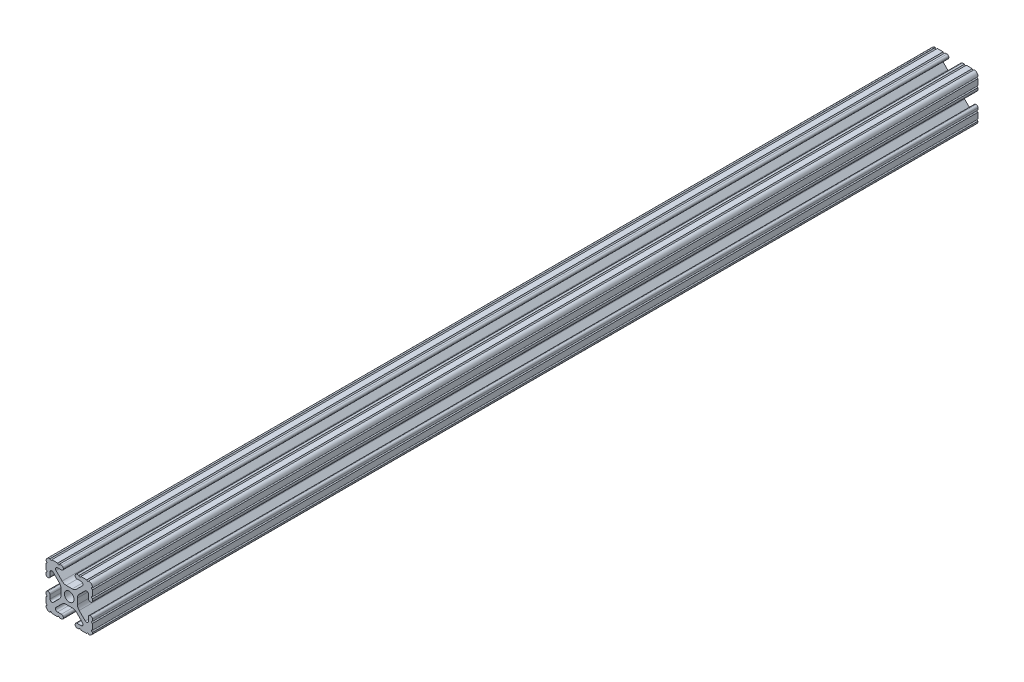
SolidWorks part; units mm, degrees
ref_plane "Front Plane" through (0, 0, 0) normal (0, 0, 1) x (1, 0, 0)
ref_plane "Top Plane" through (0, 0, 0) normal (0, 1, 0) x (1, 0, 0)
ref_plane "Right Plane" through (0, 0, 0) normal (1, 0, 0) x (0, 0, -1)
sketch "Sketch1" plane through (0, 0, 0) normal (0, 0, 1) x (1, 0, 0)
  line L88 (-7.1797, -8.6452) -> (-3.9523, -5.4237)
  line L89 (-1.7093, -4.4958) -> (1.7093, -4.4958)
  line L90 (3.9523, -5.4237) -> (7.1797, -8.6452)
  line L91 (6.4164, -10.4902) -> (4.2875, -10.4902)
  line L92 (3.2385, -11.5392) -> (3.2385, -11.651)
  line L93 (4.2875, -12.7) -> (5.3171, -12.7)
  line L94 (6.3331, -12.7) -> (9.5504, -12.7)
  line L95 (12.7, -9.5504) -> (12.7, -6.3331)
  line L96 (12.7, -5.3171) -> (12.7, -4.2875)
  line L97 (11.651, -3.2385) -> (11.5392, -3.2385)
  line L98 (10.4902, -4.2875) -> (10.4902, -6.4021)
  line L99 (8.7371, -7.1294) -> (5.441, -3.8408)
  line L100 (4.5085, -1.5932) -> (4.5085, 1.5932)
  line L101 (5.441, 3.8408) -> (8.7371, 7.1294)
  line L102 (10.4902, 6.4021) -> (10.4902, 4.2875)
  line L103 (11.5392, 3.2385) -> (11.651, 3.2385)
  line L104 (12.7, 4.2875) -> (12.7, 5.3171)
  line L105 (12.7, 6.3331) -> (12.7, 9.5504)
  line L106 (9.5504, 12.7) -> (6.3331, 12.7)
  line L107 (5.3171, 12.7) -> (4.2875, 12.7)
  line L108 (3.2385, 11.651) -> (3.2385, 11.5392)
  line L109 (4.2875, 10.4902) -> (6.4768, 10.4902)
  line L110 (7.207, 8.7244) -> (3.8983, 5.4232)
  line L111 (1.6558, 4.4958) -> (-1.6558, 4.4958)
  line L112 (-3.8983, 5.4232) -> (-7.207, 8.7244)
  line L113 (-6.4768, 10.4902) -> (-4.2875, 10.4902)
  line L114 (-3.2385, 11.5392) -> (-3.2385, 11.651)
  line L115 (-4.2875, 12.7) -> (-5.3171, 12.7)
  line L116 (-6.3331, 12.7) -> (-9.5504, 12.7)
  line L117 (-12.7, 9.5504) -> (-12.7, 6.3331)
  line L118 (-12.7, 5.3171) -> (-12.7, 4.2875)
  line L119 (-11.651, 3.2385) -> (-11.5392, 3.2385)
  line L120 (-10.4902, 4.2875) -> (-10.4902, 6.4021)
  line L121 (-8.7371, 7.1294) -> (-5.441, 3.8408)
  line L122 (-4.5085, 1.5932) -> (-4.5085, -1.5932)
  line L123 (-5.441, -3.8408) -> (-8.7371, -7.1294)
  line L124 (-10.4902, -6.4021) -> (-10.4902, -4.2875)
  line L125 (-11.5392, -3.2385) -> (-11.651, -3.2385)
  line L126 (-12.7, -4.2875) -> (-12.7, -5.3171)
  line L127 (-12.7, -6.3331) -> (-12.7, -9.5504)
  line L128 (-9.5504, -12.7) -> (-6.3331, -12.7)
  line L129 (-5.3171, -12.7) -> (-4.2875, -12.7)
  line L130 (-3.2385, -11.651) -> (-3.2385, -11.5392)
  line L131 (-4.2875, -10.4902) -> (-6.4164, -10.4902)
  circle A1 centre (0, 0) radius 2.6035
  arc A104 (-7.1797, -8.6452) -> (-6.4164, -10.4902) centre (-6.4164, -9.4098) ccw
  arc A105 (-1.7093, -4.4958) -> (-3.9523, -5.4237) centre (-1.7093, -7.6708) ccw
  arc A106 (3.9523, -5.4237) -> (1.7093, -4.4958) centre (1.7093, -7.6708) ccw
  arc A107 (6.4164, -10.4902) -> (7.1797, -8.6452) centre (6.4164, -9.4098) ccw
  arc A108 (4.2875, -10.4902) -> (3.2385, -11.5392) centre (4.2875, -11.5392) ccw
  arc A109 (3.2385, -11.651) -> (4.2875, -12.7) centre (4.2875, -11.651) ccw
  arc A110 (6.3331, -12.7) -> (5.3171, -12.7) centre (5.8251, -12.7) ccw
  arc A111 (10.5664, -12.6998) -> (9.5504, -12.7) centre (10.0584, -12.7) ccw
  arc A112 (10.5664, -12.6998) -> (12.6998, -10.5664) centre (10.5918, -10.5918) ccw
  arc A113 (12.7, -9.5504) -> (12.6998, -10.5664) centre (12.7, -10.0584) ccw
  arc A114 (12.7, -5.3171) -> (12.7, -6.3331) centre (12.7, -5.8251) ccw
  arc A115 (12.7, -4.2875) -> (11.651, -3.2385) centre (11.651, -4.2875) ccw
  arc A116 (11.5392, -3.2385) -> (10.4902, -4.2875) centre (11.5392, -4.2875) ccw
  arc A117 (8.7371, -7.1294) -> (10.4902, -6.4021) centre (9.4628, -6.4021) ccw
  arc A118 (4.5085, -1.5932) -> (5.441, -3.8408) centre (7.6835, -1.5932) ccw
  arc A119 (5.441, 3.8408) -> (4.5085, 1.5932) centre (7.6835, 1.5932) ccw
  arc A120 (10.4902, 6.4021) -> (8.7371, 7.1294) centre (9.4628, 6.4021) ccw
  arc A121 (10.4902, 4.2875) -> (11.5392, 3.2385) centre (11.5392, 4.2875) ccw
  arc A122 (11.651, 3.2385) -> (12.7, 4.2875) centre (11.651, 4.2875) ccw
  arc A123 (12.7, 6.3331) -> (12.7, 5.3171) centre (12.7, 5.8251) ccw
  arc A124 (12.6998, 10.5664) -> (12.7, 9.5504) centre (12.7, 10.0584) ccw
  arc A125 (12.6998, 10.5664) -> (10.5664, 12.6998) centre (10.5918, 10.5918) ccw
  arc A126 (9.5504, 12.7) -> (10.5664, 12.6998) centre (10.0584, 12.7) ccw
  arc A127 (5.3171, 12.7) -> (6.3331, 12.7) centre (5.8251, 12.7) ccw
  arc A128 (4.2875, 12.7) -> (3.2385, 11.651) centre (4.2875, 11.651) ccw
  arc A129 (3.2385, 11.5392) -> (4.2875, 10.4902) centre (4.2875, 11.5392) ccw
  arc A130 (7.207, 8.7244) -> (6.4768, 10.4902) centre (6.4768, 9.4563) ccw
  arc A131 (1.6558, 4.4958) -> (3.8983, 5.4232) centre (1.6558, 7.6708) ccw
  arc A132 (-3.8983, 5.4232) -> (-1.6558, 4.4958) centre (-1.6558, 7.6708) ccw
  arc A133 (-6.4768, 10.4902) -> (-7.207, 8.7244) centre (-6.4768, 9.4563) ccw
  arc A134 (-4.2875, 10.4902) -> (-3.2385, 11.5392) centre (-4.2875, 11.5392) ccw
  arc A135 (-3.2385, 11.651) -> (-4.2875, 12.7) centre (-4.2875, 11.651) ccw
  arc A136 (-6.3331, 12.7) -> (-5.3171, 12.7) centre (-5.8251, 12.7) ccw
  arc A137 (-10.5664, 12.6998) -> (-9.5504, 12.7) centre (-10.0584, 12.7) ccw
  arc A138 (-10.5664, 12.6998) -> (-12.6998, 10.5664) centre (-10.5918, 10.5918) ccw
  arc A139 (-12.7, 9.5504) -> (-12.6998, 10.5664) centre (-12.7, 10.0584) ccw
  arc A140 (-12.7, 5.3171) -> (-12.7, 6.3331) centre (-12.7, 5.8251) ccw
  arc A141 (-12.7, 4.2875) -> (-11.651, 3.2385) centre (-11.651, 4.2875) ccw
  arc A142 (-11.5392, 3.2385) -> (-10.4902, 4.2875) centre (-11.5392, 4.2875) ccw
  arc A143 (-8.7371, 7.1294) -> (-10.4902, 6.4021) centre (-9.4628, 6.4021) ccw
  arc A144 (-4.5085, 1.5932) -> (-5.441, 3.8408) centre (-7.6835, 1.5932) ccw
  arc A145 (-5.441, -3.8408) -> (-4.5085, -1.5932) centre (-7.6835, -1.5932) ccw
  arc A146 (-10.4902, -6.4021) -> (-8.7371, -7.1294) centre (-9.4628, -6.4021) ccw
  arc A147 (-10.4902, -4.2875) -> (-11.5392, -3.2385) centre (-11.5392, -4.2875) ccw
  arc A148 (-11.651, -3.2385) -> (-12.7, -4.2875) centre (-11.651, -4.2875) ccw
  arc A149 (-12.7, -6.3331) -> (-12.7, -5.3171) centre (-12.7, -5.8251) ccw
  arc A150 (-12.6998, -10.5664) -> (-12.7, -9.5504) centre (-12.7, -10.0584) ccw
  arc A151 (-12.6998, -10.5664) -> (-10.5664, -12.6998) centre (-10.5918, -10.5918) ccw
  arc A152 (-9.5504, -12.7) -> (-10.5664, -12.6998) centre (-10.0584, -12.7) ccw
  arc A153 (-5.3171, -12.7) -> (-6.3331, -12.7) centre (-5.8251, -12.7) ccw
  arc A154 (-4.2875, -12.7) -> (-3.2385, -11.651) centre (-4.2875, -11.651) ccw
  arc A155 (-3.2385, -11.5392) -> (-4.2875, -10.4902) centre (-4.2875, -11.5392) ccw
extrude "Boss-Extrude1" add sketch "Sketch1" along normal mid plane 609.6
sketch "Sketch2" plane through (0, 0, 304.8) normal (0, 0, 1) x (1, 0, 0)
  line L1 (-15.2069, 16.5389) -> (14.8739, 16.5389)
  line L2 (-15.2069, 16.5389) -> (-15.2069, -15.8729)
  line L3 (-15.2069, -15.8729) -> (14.8739, -15.8729)
  line L4 (14.8739, 16.5389) -> (14.8739, -15.8729)
extrude "Cut-Extrude1" cut sketch "Sketch2" against normal blind 125.73
